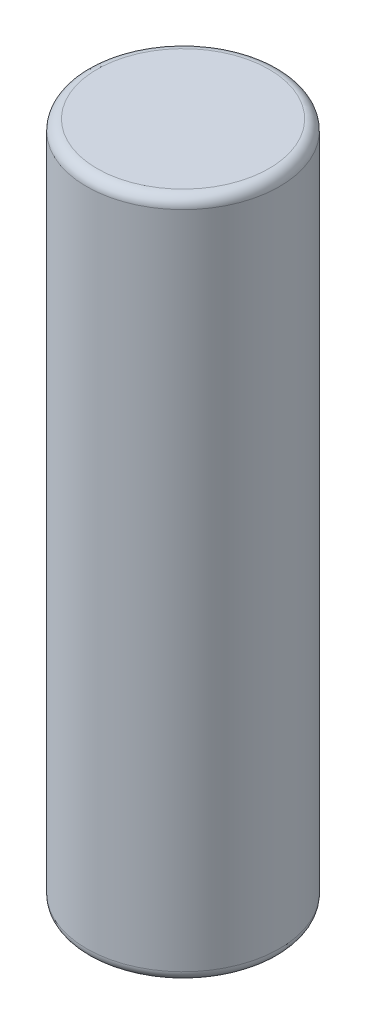
SolidWorks part; units mm, degrees
material "1060 Alloy"
ref_plane "정면" through (0, 0, 0) normal (0, 0, 1) x (1, 0, 0)
ref_plane "윗면" through (0, 0, 0) normal (0, 1, 0) x (1, 0, 0)
ref_plane "우측면" through (0, 0, 0) normal (1, 0, 0) x (0, 0, -1)
sketch "스케치1" plane through (0, 0, 0) normal (0, 1, 0) x (1, 0, 0)
  circle A0 centre (0, 0) radius 9.25
  dimension "D1" = 18.5
extrude "보스-돌출1" add sketch "스케치1" along normal mid plane 65.3
fillet "필렛1" radius 1 2 edges at (0, -32.65, 9.25) (0, 32.65, 9.25)
